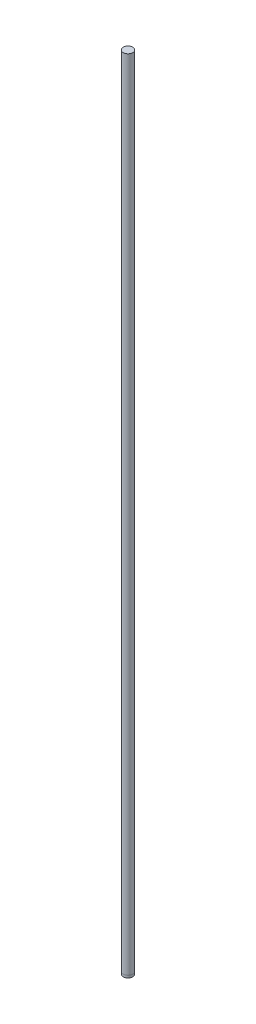
SolidWorks part; units mm, degrees
material "Balsa"
ref_plane "Front Plane" through (0, 0, 0) normal (0, 0, 1) x (1, 0, 0)
ref_plane "Top Plane" through (0, 0, 0) normal (0, 1, 0) x (1, 0, 0)
ref_plane "Right Plane" through (0, 0, 0) normal (1, 0, 0) x (0, 0, -1)
sketch "Sketch1" plane through (0, 0, 0) normal (0, 1, 0) x (1, 0, 0)
  circle A0 centre (0, 0) radius 6
  dimension "D1" = 12
extrude "Boss-Extrude1" add sketch "Sketch1" along normal blind 1000
sketch "Sketch2" plane through (0, 0, 0) normal (0, -1, 0) x (-1, 0, 0)
  circle A0 centre (0, 0) radius 6
extrude "Boss-Extrude2" add sketch "Sketch2" along normal blind 3
sketch "Sketch3" plane through (0, -3, 0) normal (0, -1, 0) x (-1, 0, 0)
  circle A0 centre (0, 0) radius 5.9708
extrude "Boss-Extrude3" add sketch "Sketch3" along normal blind 3
